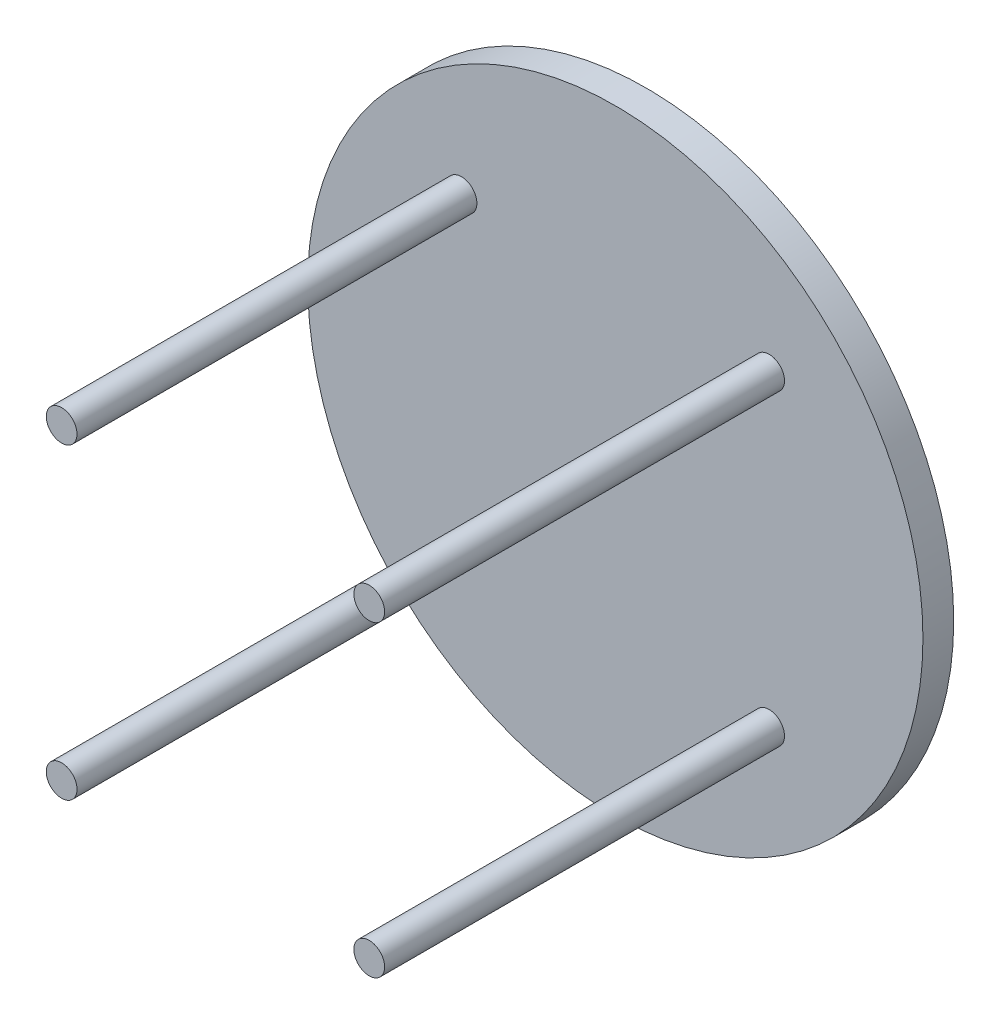
SolidWorks part; units mm, degrees
ref_plane "前视基准面" through (0, 0, 0) normal (0, 0, 1) x (1, 0, 0)
ref_plane "上视基准面" through (0, 0, 0) normal (0, 1, 0) x (1, 0, 0)
ref_plane "右视基准面" through (0, 0, 0) normal (1, 0, 0) x (0, 0, -1)
other "Configuration Table"
sketch "草图1" plane through (0, 0, 0) normal (0, 0, 1) x (1, 0, 0)
  circle A0 centre (0, 0) radius 500
extrude "凸台-拉伸1" add sketch "草图1" along normal blind 50
sketch "草图2" plane through (0, 0, 0) normal (0, 0, 1) x (1, 0, 0)
  circle A0 centre (250, 250) radius 25
extrude "凸台-拉伸2" add sketch "草图2" along normal blind 700
sketch "草图3" plane through (0, 0, 0) normal (0, 0, 1) x (1, 0, 0)
  circle A0 centre (-250, 250) radius 25
extrude "凸台-拉伸3" add sketch "草图3" along normal blind 700
sketch "草图4" plane through (0, 0, 0) normal (0, 0, 1) x (1, 0, 0)
  circle A0 centre (250, -250) radius 25
extrude "凸台-拉伸4" add sketch "草图4" along normal blind 700
sketch "草图5" plane through (0, 0, 0) normal (0, 0, 1) x (1, 0, 0)
  circle A0 centre (-250, -250) radius 25
extrude "凸台-拉伸5" add sketch "草图5" along normal blind 700
